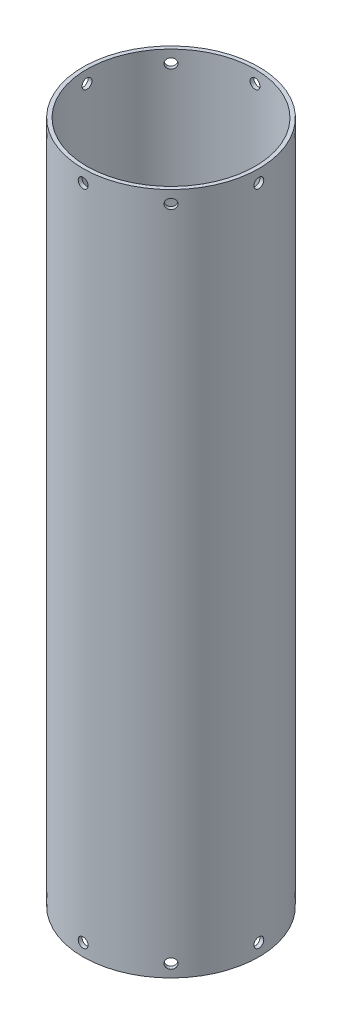
SolidWorks part; units mm, degrees
material "6061-T6 (SS)"
ref_plane "Front Plane" through (0, 0, 0) normal (0, 0, 1) x (1, 0, 0)
ref_plane "Top Plane" through (0, 0, 0) normal (0, 1, 0) x (1, 0, 0)
ref_plane "Right Plane" through (0, 0, 0) normal (1, 0, 0) x (0, 0, -1)
sketch "Sketch1" plane through (0, 0, 0) normal (0, 1, 0) x (1, 0, 0)
  circle A0 centre (0, 0) radius 89.2948
  circle A1 centre (0, 0) radius 85.4254
  dimension "D1" = 178.5897
  dimension "D2" = 3.8694
extrude "Boss-Extrude1" add sketch "Sketch1" along normal blind 693.1406
sketch "Sketch2" plane through (0, 667.7406, 0) normal (1, 0, 0) x (0, 0, 1)
  circle A0 centre (0, -12.7) radius 4.7625 construction
  circle A1 centre (0, -12.7) radius 4.7625 construction
  circle A2 centre (0, -12.7) radius 5.0165
  dimension "D1" = 0.254
extrude "LOX Top Holes" cut sketch "Sketch2" along normal up to surface (89.1538 mm away) contours A2
pattern_circular "CirPattern1" count 8 over 360 about axis through (0, 693.1406, 0) along (0, 1, 0) of "LOX Top Holes"
sketch "Sketch3" plane through (0, 25.4, 0) normal (1, 0, 0) x (0, 0, -1)
  circle A0 centre (0, -12.7) radius 4.7625 construction
  circle A1 centre (0, -12.7) radius 4.7625 construction
  circle A2 centre (0, -12.7) radius 5.0165
  dimension "D1" = 0.254
extrude "LOX Bottom Holes" cut sketch "Sketch3" along normal up to surface (89.1538 mm away) contours A2
pattern_circular "CirPattern2" count 8 over 360 about axis through (0, 0, 0) along (0, 1, 0) of "LOX Bottom Holes"
sketch "Sketch4" [suppressed] plane through (0, 442.595, 0) normal (1, 0, 0) x (0, 0, 1)
  circle A0 centre (0, -12.7) radius 4.7625 construction
  circle A1 centre (0, -12.7) radius 4.7625 construction
  circle A2 centre (0, -12.7) radius 5.0165
  dimension "D1" = 0.254
extrude "Cut-Extrude1" [suppressed] cut sketch "Sketch4" along normal up to surface (76.0347 mm away) contours A2
pattern_circular "CirPattern3" [suppressed] count 8 over 360
sketch "Sketch7" [suppressed] plane through (0, 25.4, 0) normal (1, 0, 0) x (0, 0, -1)
  circle A0 centre (0, -12.7) radius 4.7625 construction
  circle A1 centre (0, -12.7) radius 4.7625 construction
  circle A2 centre (0, -12.7) radius 5.0165
  dimension "D1" = 0.254
extrude "Cut-Extrude2" [suppressed] cut sketch "Sketch7" along normal up to surface (76.0347 mm away)
pattern_circular "CirPattern4" [suppressed] count 8 over 360
scale "Scale1" scale about centroid uniform scaling yes scale factor 0.426676
